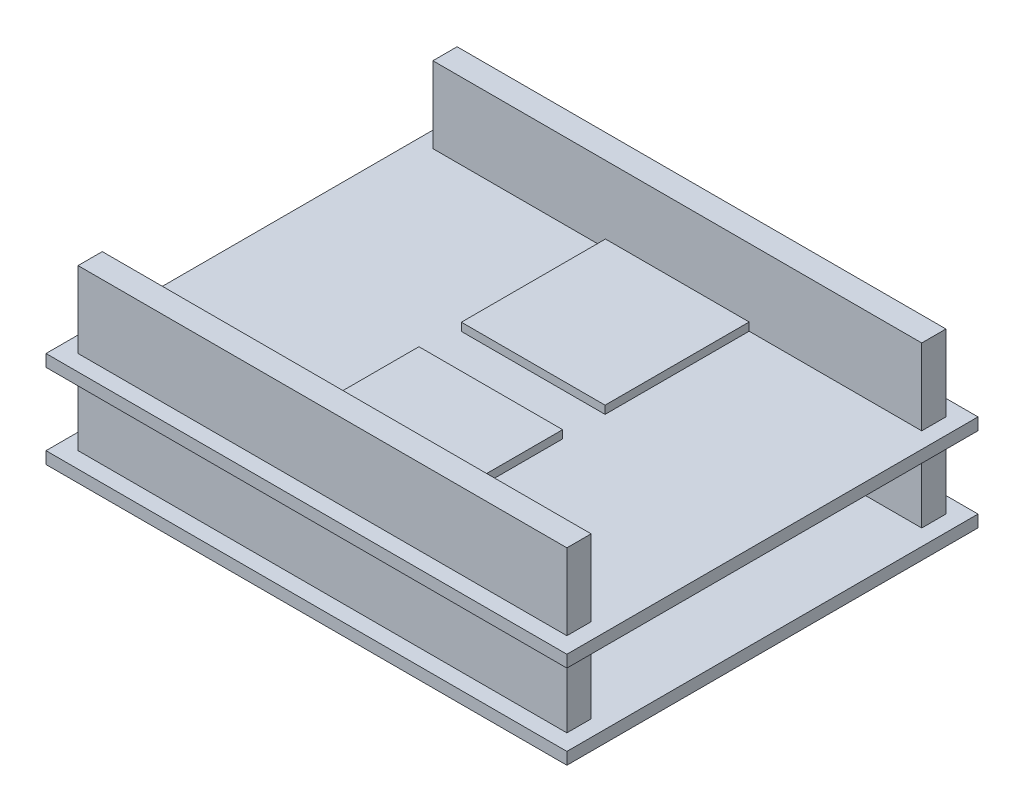
SolidWorks part; units mm, degrees
ref_plane "Front Plane" through (0, 0, 0) normal (0, 0, 1) x (1, 0, 0)
ref_plane "Top Plane" through (0, 0, 0) normal (0, 1, 0) x (1, 0, 0)
ref_plane "Right Plane" through (0, 0, 0) normal (1, 0, 0) x (0, 0, -1)
sketch "Sketch1" plane through (0, 0, 0) normal (0, 1, 0) x (1, 0, 0)
  line L1 (32.5, 25.65) -> (-32.5, 25.65)
  line L2 (32.5, 25.65) -> (32.5, -25.65)
  line L3 (32.5, -25.65) -> (-32.5, -25.65)
  line L4 (-32.5, 25.65) -> (-32.5, -25.65)
  line L5 (32.5, 25.65) -> (-32.5, -25.65) construction
  line L6 (32.5, -25.65) -> (-32.5, 25.65) construction
  point P0 (0, 0)
extrude "Boss-Extrude1" add sketch "Sketch1" along normal blind 1.5
sketch "Sketch2" plane through (0, 1.5, 0) normal (0, 1, 0) x (1, 0, 0)
  line L0 (32.5, 25.65) -> (-32.5, 25.65) construction
  line L1 (-8.9648, 20.65) -> (8.9648, 20.65)
  line L2 (-8.9648, 20.65) -> (-8.9648, 2.65)
  line L3 (-8.9648, 2.65) -> (8.9648, 2.65)
  line L4 (8.9648, 20.65) -> (8.9648, 2.65)
  line L5 (-8.9648, 20.65) -> (8.9648, 2.65) construction
  line L6 (-8.9648, 2.65) -> (8.9648, 20.65) construction
  line L7 (32.5, 0) -> (36.5118, 0) construction
  line L8 (32.5, -25.65) -> (32.5, 25.65) construction
  line L9 (-8.9648, -20.65) -> (-8.9648, -2.65)
  line L10 (-8.9648, -2.65) -> (8.9648, -2.65)
  line L11 (8.9648, -20.65) -> (8.9648, -2.65)
  line L12 (-8.9648, -20.65) -> (8.9648, -20.65)
  point P0 (0, 11.65)
  dimension "D1" = 5
  dimension "D2" = 18
extrude "Boss-Extrude2" add sketch "Sketch2" along normal blind 1
sketch "Sketch4" plane through (0, 0, 0) normal (0, -1, 0) x (1, 0, 0)
  line L0 (-32.5, 25.65) -> (32.5, 25.65) construction
  line L1 (-30.5, 23.65) -> (30.5, 23.65)
  line L2 (-30.5, 23.65) -> (-30.5, 20.6274)
  line L3 (-30.5, 20.6274) -> (30.5, 20.6274)
  line L4 (30.5, 23.65) -> (30.5, 20.6274)
  line L5 (-32.5, -25.65) -> (-32.5, 25.65) construction
  line L6 (32.5, 25.65) -> (32.5, -25.65) construction
  line L7 (0, 0) -> (-38.8475, 0) construction
  line L8 (30.5, -23.65) -> (30.5, -20.6274)
  line L9 (-30.5, -23.65) -> (30.5, -23.65)
  line L10 (-30.5, -23.65) -> (-30.5, -20.6274)
  line L11 (-30.5, -20.6274) -> (30.5, -20.6274)
  dimension "D1" = 2
  dimension "D2" = 2
  dimension "D3" = 2
extrude "Boss-Extrude3" add sketch "Sketch4" against normal blind 11 and the other way blind 9
sketch "Sketch5" plane through (0, -9, 0) normal (0, -1, 0) x (1, 0, 0)
  line L1 (-32.5, 25.65) -> (32.5, 25.65)
  line L2 (-32.5, 25.65) -> (-32.5, -25.65)
  line L3 (-32.5, -25.65) -> (32.5, -25.65)
  line L4 (32.5, 25.65) -> (32.5, -25.65)
extrude "Boss-Extrude4" add sketch "Sketch5" along normal blind 1.5
